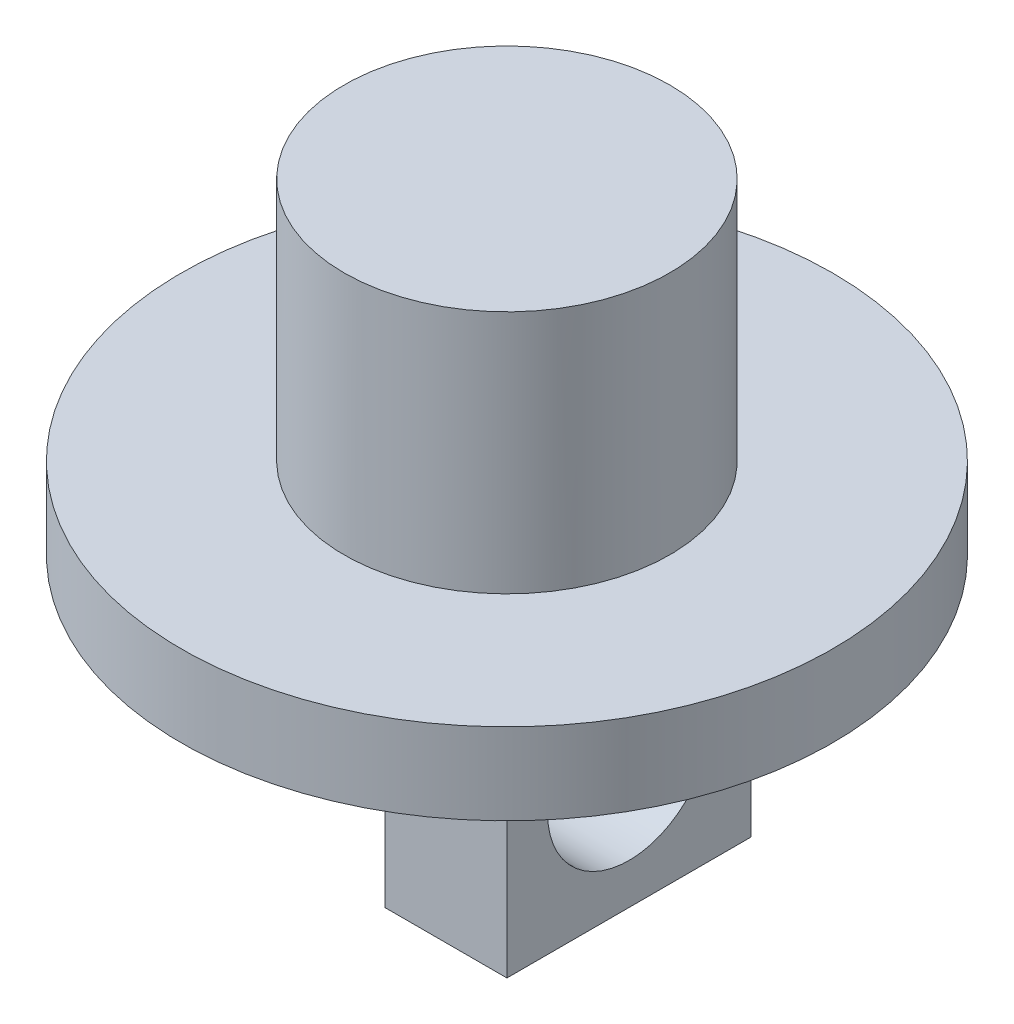
SolidWorks part; units mm, degrees
ref_plane "Front Plane" through (0, 0, 0) normal (0, 0, 1) x (1, 0, 0)
ref_plane "Top Plane" through (0, 0, 0) normal (0, 1, 0) x (1, 0, 0)
ref_plane "Right Plane" through (0, 0, 0) normal (1, 0, 0) x (0, 0, -1)
sketch "Sketch1" plane through (0, 0, 0) normal (0, 1, 0) x (1, 0, 0)
  circle A0 centre (0, 0) radius 2.54
  dimension "D1" = 5.08
extrude "Boss-Extrude1" add sketch "Sketch1" along normal blind 5.08
sketch "Sketch2" plane through (0, 0, 0) normal (0, -1, 0) x (1, 0, 0)
  circle A0 centre (0, 0) radius 5.08
  circle A1 centre (0, 0) radius 2.54 construction
  circle A2 centre (0, 0) radius 2.54
  dimension "D1" = 2.54
extrude "Boss-Extrude2" add sketch "Sketch2" against normal blind 1.27
sketch "Sketch3" plane through (0, 0, 0) normal (0, -1, 0) x (1, 0, 0)
  line L0 (0, 5.08) -> (0, -5.08) construction
  line L1 (1.905, 0) -> (0, 0) construction
  line L2 (0, 1.905) -> (1.905, 1.905)
  line L3 (0, 1.905) -> (0, -1.905)
  line L4 (0, -1.905) -> (1.905, -1.905)
  line L5 (1.905, 1.905) -> (1.905, -1.905)
  circle A0 centre (0, 0) radius 5.08 construction
  point P11 (0, 0)
  dimension "D1" = 3.81
  dimension "D2" = 1.905
extrude "Boss-Extrude3" add sketch "Sketch3" along normal blind 3.81
sketch "Sketch4" plane through (0, 0, 0) normal (-1, 0, 0) x (0, 0, 1)
  line L0 (-1.905, -3.81) -> (1.905, 0) construction
  line L1 (1.905, -3.81) -> (-1.905, 0) construction
  circle A0 centre (0, -1.905) radius 1.27
  point P8 (0, -1.905)
  dimension "D1" = 2.54
extrude "Cut-Extrude1" cut sketch "Sketch4" against normal up to next
